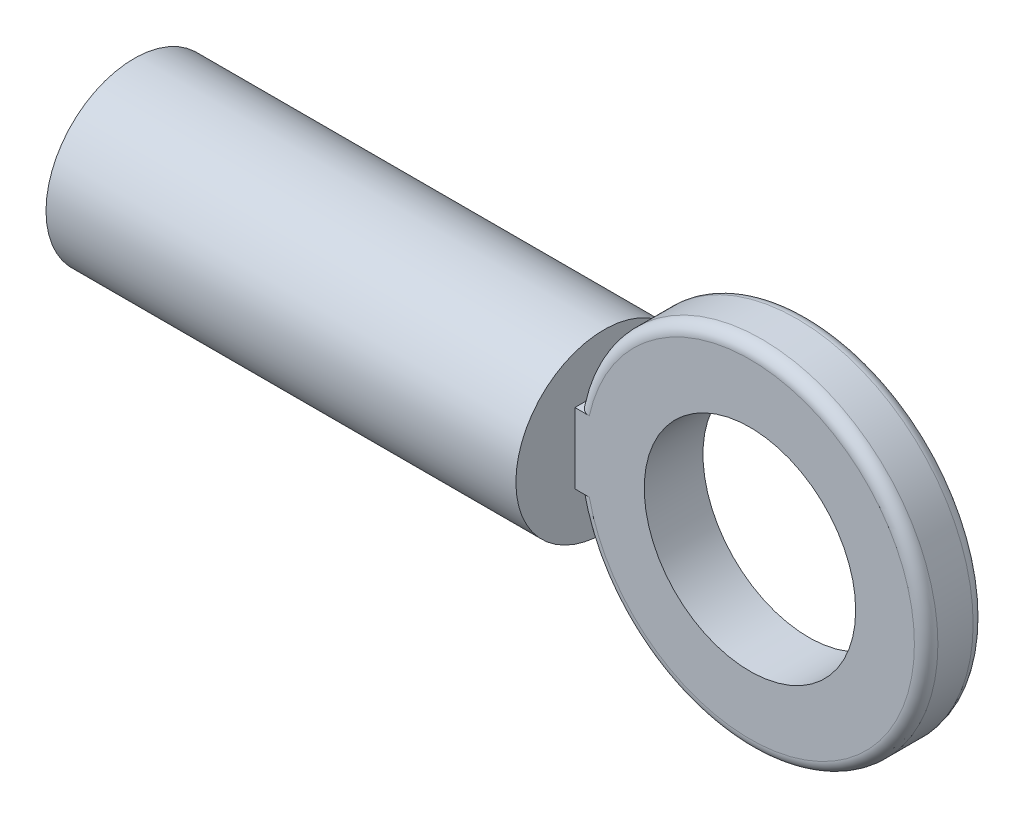
SolidWorks part; units mm, degrees
ref_plane "Front Plane" through (0, 0, 0) normal (0, 0, 1) x (1, 0, 0)
ref_plane "Top Plane" through (0, 0, 0) normal (0, 1, 0) x (1, 0, 0)
ref_plane "Right Plane" through (0, 0, 0) normal (1, 0, 0) x (0, 0, -1)
sketch "Sketch4" plane through (0, 0, 0) normal (0, 0, 1) x (1, 0, 0)
  line L0 (-54.899, -3) -> (-54.899, 3)
  line L1 (-14.6969, 3) -> (-54.899, 3)
  line L2 (-14.6969, -3) -> (-54.899, -3)
  arc A0 (-14.6969, -3) -> (-14.6969, 3) centre (0, 0) ccw
  dimension "D1" = 30
extrude "Boss-Extrude2" add sketch "Sketch4" along normal blind 5
sketch "Sketch6" plane through (0, 0, 5) normal (0, 0, 1) x (1, 0, 0)
  circle A0 centre (0, 0) radius 9
  dimension "D1" = 18
extrude "Cut-Extrude1" cut sketch "Sketch6" against normal through all
fillet "Fillet2" radius 1 2 edges at (15, 0, 0) (15, 0, 5)
sketch "Sketch7" plane through (-54.899, 0, 0) normal (-1, 0, 0) x (0, 0, 1)
  circle A0 centre (2.5281, 0) radius 7.5
  dimension "D1" = 15
extrude "Boss-Extrude3" add sketch "Sketch7" against normal blind 40
